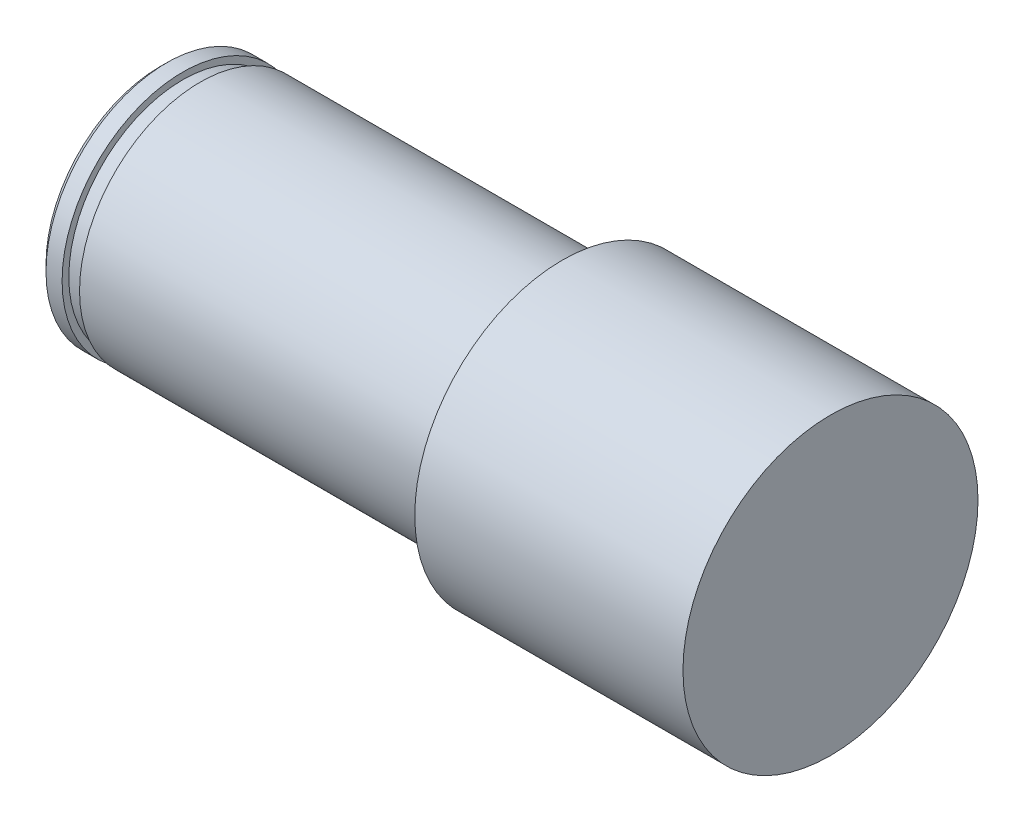
SolidWorks part; units mm, degrees
ref_plane "Plano frontal" through (0, 0, 0) normal (0, 0, 1) x (1, 0, 0)
ref_plane "Plano superior" through (0, 0, 0) normal (0, 1, 0) x (1, 0, 0)
ref_plane "Plano direito" through (0, 0, 0) normal (1, 0, 0) x (0, 0, -1)
sketch "Esboço1" plane through (0, 0, 0) normal (0, 1, 0) x (1, 0, 0)
  line L0 (0, 0) -> (0, 11)
  line L1 (0, 11) -> (-20, 11)
  line L2 (-20, 11) -> (-20, 9)
  line L3 (-20, 9) -> (-47, 9)
  line L4 (-47, 9) -> (-47, 8.5)
  line L5 (-47, 8.5) -> (-48.3, 8.5)
  line L6 (-48.3, 8.5) -> (-48.3, 9)
  line L7 (-48.3, 9) -> (-50, 9)
  line L9 (-50, 9) -> (-50, 0)
  line L10 (-50, 0) -> (0, 0) construction
  line L11 (0, 0) -> (-50, 0)
  point P3 (-59.061, 14.554)
  point P11 (-45.7, 15.4802)
  dimension "D1" = 20
  dimension "D2" = 27
  dimension "D3" = 50
  dimension "D4" = 11
  dimension "D5" = 9
  dimension "D6" = 1.3
  dimension "D7" = 9
  dimension "D8" = 17
revolve "Revolução1" add sketch "Esboço1" angle 360 about L10
chamfer "Chanfro1" distance 0.5 angle 45 1 edges at (-50, 0, 9)
ref_plane "Plano1" through (0, 10, 0) normal (0, 1, 0) x (1, 0, 0)
sketch "Esboço2" plane through (0, 10, 0) normal (0, 1, 0) x (1, 0, 0)
  line L1 (-43.6, 2.6168) -> (-23.6, 2.6168)
  line L2 (-43.6, 2.6168) -> (-43.6, -3.3832)
  line L3 (-43.6, -3.3832) -> (-23.6, -3.3832)
  line L4 (-23.6, 2.6168) -> (-23.6, -3.3832)
  dimension "D1" = 20
  dimension "D2" = 3.6
  dimension "D3" = 6
